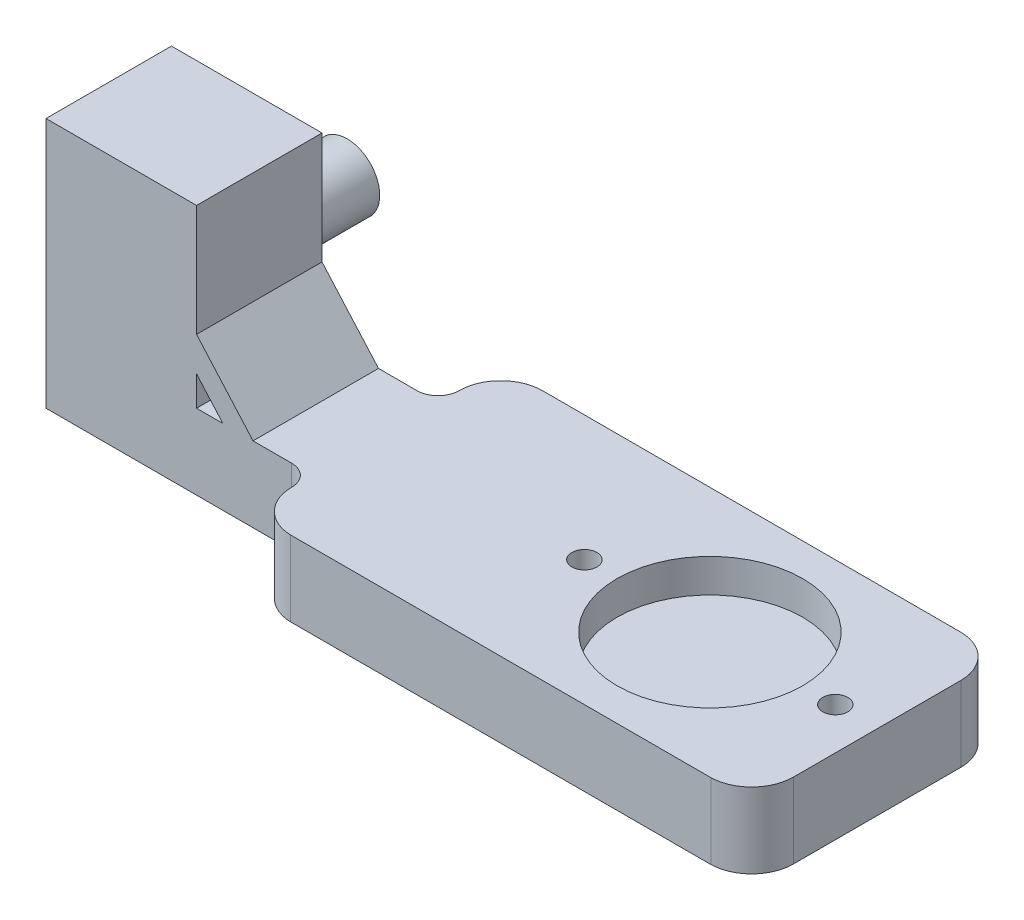
SolidWorks part; units mm, degrees
ref_plane "Front Plane" through (0, 0, 0) normal (0, 0, 1) x (1, 0, 0)
ref_plane "Top Plane" through (0, 0, 0) normal (0, 1, 0) x (1, 0, 0)
ref_plane "Right Plane" through (0, 0, 0) normal (1, 0, 0) x (0, 0, -1)
sketch "Sketch1" plane through (0, 0, 0) normal (0, 1, 0) x (1, 0, 0)
  line L0 (-25, 11.3509) -> (25, 11.3509)
  line L1 (30, 6.3509) -> (30, -13.6505)
  line L2 (25.1211, -18.6491) -> (-25.1211, -18.6491)
  line L3 (0, 15.519) -> (0, -21.8512) construction
  line L5 (-32.5, 3.8509) -> (-43.8692, 3.8509)
  line L6 (-43.8692, 3.8509) -> (-43.8692, -11.1491)
  line L7 (-43.8692, -11.1491) -> (-32.5, -11.1491)
  arc A0 (25, 11.3509) -> (30, 6.3509) centre (25, 6.3509) cw
  arc A1 (30, -13.6505) -> (25.1211, -18.6491) centre (25, -13.6505) cw
  arc A2 (-30, -13.6505) -> (-25.1211, -18.6491) centre (-25, -13.6505) ccw
  arc A3 (-25, 11.3509) -> (-30, 6.3509) centre (-25, 6.3509) ccw
  arc A4 (-30, 6.3509) -> (-32.5, 3.8509) centre (-32.5, 6.3509) cw
  arc A5 (-32.5, -11.1491) -> (-30, -13.6505) centre (-32.5, -13.6491) cw
  point P12 (0, -18.6491)
  point P17 (0, 11.3509)
  dimension "D4" = 5
  dimension "D5" = 5
  dimension "D1" = 2.5
  dimension "D6" = 2.5
  dimension "D2" = 60
  dimension "D3" = 30
  dimension "D7" = 15
extrude "Boss-Extrude1" add sketch "Sketch1" along normal blind 9
sketch "Sketch2" plane through (0, 0, 0) normal (0, 1, 0) x (1, 0, 0)
  line L0 (-45.8692, -11.1491) -> (-59.8692, -11.1491)
  line L1 (-61.8692, -9.1491) -> (-61.8692, 3.8509)
  line L2 (-59.8692, 3.8509) -> (-45.8692, 3.8509)
  line L3 (-43.8692, 3.8509) -> (-43.8692, -4.1491)
  line L4 (-61.8692, -9.1491) -> (-61.8692, -11.1491)
  line L5 (-43.8692, 3.8509) -> (-43.8692, -9.1491)
  line L6 (-45.8692, -11.1491) -> (-43.8692, -11.1491)
  line L7 (-43.8692, -11.1491) -> (-43.8692, -9.1491)
  line L8 (-61.8692, -11.1491) -> (-59.8692, -11.1491)
  line L9 (-61.8692, 3.8509) -> (-59.8692, 3.8509)
  line L11 (-45.8692, 3.8509) -> (-43.8692, 3.8509)
  point P10 (-61.8692, 3.8509)
  point P13 (-61.8692, -11.1491)
  point P16 (-43.8692, -11.1491)
  dimension "D1" = 18
  dimension "D2" = 15
sketch "Sketch3" plane through (0, 9, 0) normal (0, 1, 0) x (1, 0, 0)
  line L0 (30, -13.6505) -> (30, 6.3509) construction
  circle A0 centre (10, -3.6498) radius 11.1
  circle A1 centre (25, -3.6498) radius 1.5
  circle A2 centre (-5, -3.6498) radius 1.5
  dimension "D1" = 22.2
  dimension "D5" = 3
  dimension "D6" = 3
  dimension "D2" = 20
  dimension "D3" = 15
  dimension "D4" = 15
extrude "Cut-Extrude1" cut sketch "Sketch3" against normal blind 4 contours A0 | A2 | A1
extrude "Boss-Extrude2" add sketch "Sketch2" along normal blind 30
sketch "Sketch6" plane through (0, 0, 11.1491) normal (0, 0, 1) x (1, 0, 0)
  line L0 (-43.8692, 12.5585) -> (-40.727, 9)
  line L1 (-43.8692, 30) -> (-43.8692, 9) construction
  line L2 (-37.1156, 9) -> (-43.8692, 16.6484)
  line L3 (-43.8692, 9) -> (-32.5, 9) construction
  line L4 (-43.8692, 16.6484) -> (-43.8692, 12.5585)
  line L5 (-40.727, 9) -> (-37.1156, 9)
extrude "Boss-Extrude4" add sketch "Sketch6" against normal up to surface (15 mm away) up to face at (-46.0795, 13, -3.8509)
sketch "Sketch7" plane through (0, 0, -3.8509) normal (0, 0, -1) x (-1, 0, 0)
  circle A0 centre (52.8692, 15) radius 3.9
  dimension "D1" = 7.8
extrude "Boss-Extrude5" add sketch "Sketch7" along normal blind 12
